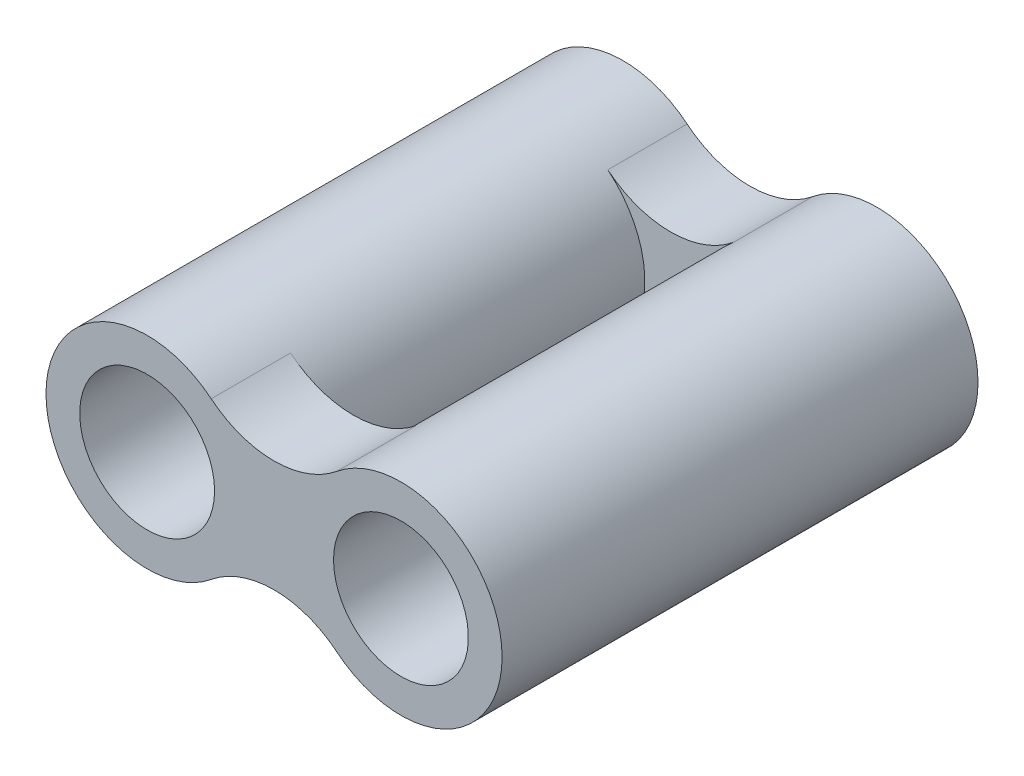
SolidWorks part; units mm, degrees
material "AISI 304"
ref_plane "Alzado" through (0, 0, 0) normal (0, 0, 1) x (1, 0, 0)
ref_plane "Planta" through (0, 0, 0) normal (0, 1, 0) x (1, 0, 0)
ref_plane "Vista lateral" through (0, 0, 0) normal (1, 0, 0) x (0, 0, -1)
sketch "Croquis1" plane through (0, 0, 0) normal (0, 0, 1) x (1, 0, 0)
  line L0 (0, 18.4869) -> (0, 1.4067) construction
  line L1 (-24.1051, 0) -> (21.976, 0) construction
  line L2 (0, -1.4067) -> (0, -17.3193) construction
  arc A6 (-1.5842, 1.9727) -> (-1.5842, -1.9727) centre (-3.2, 0) ccw
  circle A7 centre (-3.2, 0) radius 1.7
  circle A8 centre (3.2, 0) radius 1.7
  arc A9 (1.5842, 1.9727) -> (1.5842, -1.9727) centre (3.2, 0) cw
  arc A10 (-1.5842, 1.9727) -> (1.5842, 1.9727) centre (0, 3.9067) ccw
  arc A11 (-1.5842, -1.9727) -> (1.5842, -1.9727) centre (0, -3.9067) cw
  point P16 (3.35, -2.3511)
  dimension "D1" = 3.4
  dimension "D2" = 2.55
  dimension "D3" = 6.4
  dimension "D4" = 2.5
extrude "Saliente-Extruir1" add sketch "Croquis1" along normal blind 2
sketch "Croquis2" plane through (0, 0, 2) normal (0, 0, 1) x (1, 0, 0)
  circle A0 centre (3.2, 0) radius 1.7 construction
  circle A1 centre (-3.2, 0) radius 1.7 construction
  circle A2 centre (3.2, 0) radius 1.7
  circle A3 centre (-3.2, 0) radius 1.7
  arc A4 (-1.5842, 1.9727) -> (1.5842, 1.9727) centre (0, 3.9067) ccw
  arc A5 (-1.5842, 1.9727) -> (-1.5842, -1.9727) centre (-3.2, 0) ccw
  arc A6 (1.5842, -1.9727) -> (-1.5842, -1.9727) centre (0, -3.9067) ccw
  arc A7 (1.5842, -1.9727) -> (1.5842, 1.9727) centre (3.2, 0) ccw
  arc A8 (-1.5842, 1.9727) -> (1.5842, 1.9727) centre (0, 3.9067) ccw
  arc A9 (-1.5842, 1.9727) -> (-1.5842, -1.9727) centre (-3.2, 0) ccw
  arc A10 (1.5842, -1.9727) -> (-1.5842, -1.9727) centre (0, -3.9067) ccw
  arc A11 (1.5842, -1.9727) -> (1.5842, 1.9727) centre (3.2, 0) ccw
  circle A12 centre (-3.2, 0) radius 2.55
  circle A13 centre (3.2, 0) radius 2.55
  circle M5 centre (-3.2, 0) radius 1.7
  circle M10 centre (3.2, 0) radius 1.7
  dimension "D2" = 5.1
  dimension "D1" = 0
extrude "Saliente-Extruir2" add sketch "Croquis2" along normal blind 8 contours A12 M5 | A13 M10
ref_plane "Plano1" through (0, 0, 6) normal (0, 0, 1) x (1, 0, 0)
mirror "Simetría1" about plane through (0, 0, 6) normal (0, 0, 1) of "Saliente-Extruir1"
